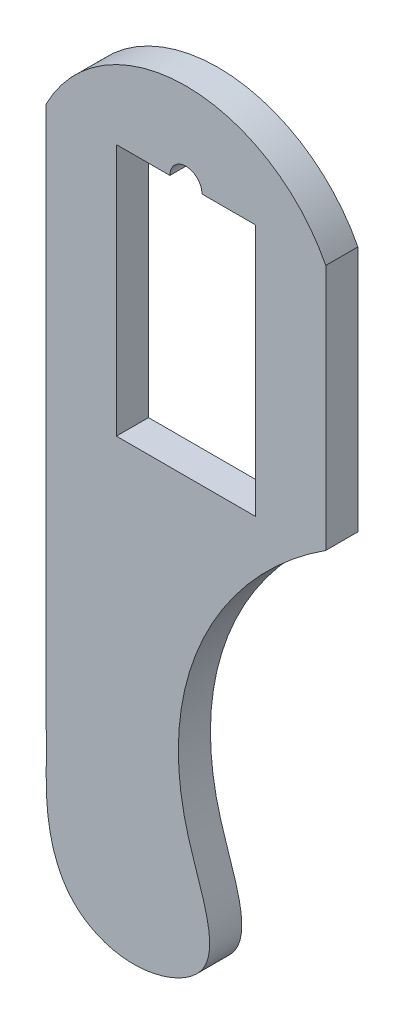
SolidWorks part; units mm, degrees
ref_plane "Front Plane" through (0, 0, 0) normal (0, 0, 1) x (1, 0, 0)
ref_plane "Top Plane" through (0, 0, 0) normal (0, 1, 0) x (1, 0, 0)
ref_plane "Right Plane" through (0, 0, 0) normal (1, 0, 0) x (0, 0, -1)
sketch "Sketch1" plane through (0, 0, 0) normal (0, 0, 1) x (1, 0, 0)
  line L0 (-13.069, 11.8) -> (-13.069, -38.2)
  line L1 (-6.5, 11.8) -> (-1.5, 11.8)
  line L2 (-6.5, 11.8) -> (-6.5, -11.8)
  line L3 (-6.5, -11.8) -> (6.5, -11.8)
  line L4 (6.5, 11.8) -> (6.5, -11.8)
  line L5 (-6.5, 11.8) -> (6.5, -11.8) construction
  line L6 (-6.5, -11.8) -> (6.5, 11.8) construction
  line L7 (-6.5, 11.8) -> (-13.069, 11.8) construction
  line L8 (13.069, 11.8) -> (13.069, -11.2134)
  line L9 (0, 11.8) -> (0, 19.8) construction
  line L10 (40.036, 310.2292) -> (346.7026, 310.2292) construction
  line L11 (13.069, -11.2134) -> (13.069, -11.2692)
  line L12 (1.5, 11.8) -> (6.5, 11.8)
  arc A0 (13.069, 11.8) -> (-13.069, 11.8) centre (0, 5.1251) ccw
  arc A1 (1.5, 11.8) -> (-1.5, 11.8) centre (0, 11.8) ccw
  spline S0 degree 3 poles (-13.069, -38.2) (-12.951, -40.9543) (-13.4632, -45.3957) (-11.1701, -52.0502) (-4.8419, -54.7869) (4.6247, -50.9252) (-5.3828, -31.8296) (3.7998, -17.2277) (13.069, -11.2692) knots 0 0 0 0 0.116411 0.189881 0.27926 0.381967 0.527064 1 1 1 1
  point P0 (0, 0)
  dimension "D7" = 3
  dimension "D1" = 23.6
  dimension "D2" = 13
  dimension "D3" = 50
  dimension "D4" = 6.569
  dimension "D5" = 6.569
  dimension "D6" = 8
extrude "Boss-Extrude1" add sketch "Sketch1" along normal blind 3
